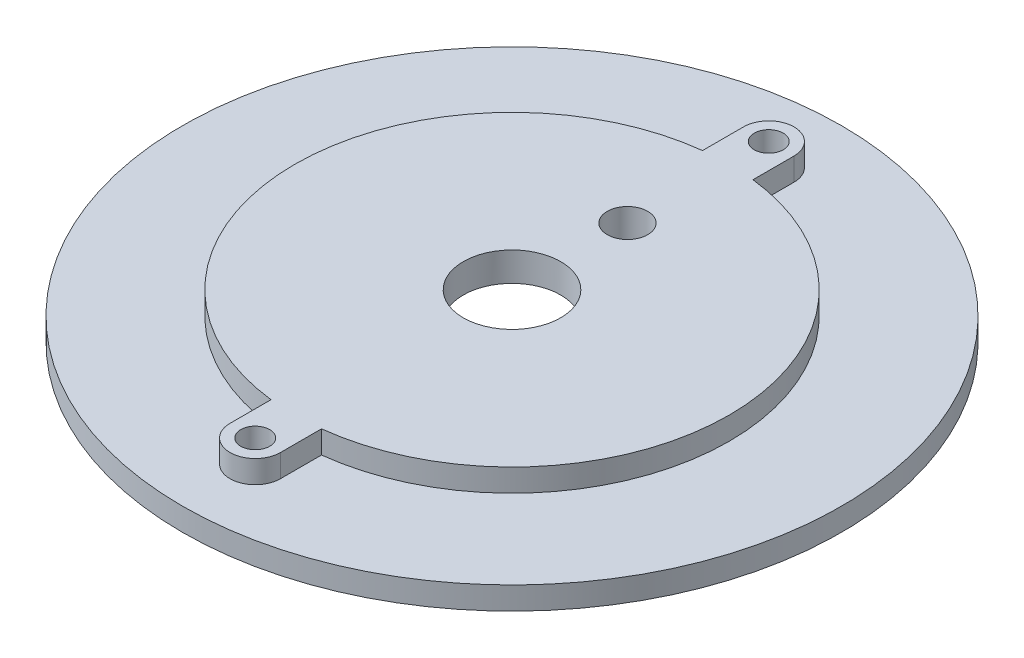
SolidWorks part; units mm, degrees
ref_plane "Front Plane" through (0, 0, 0) normal (0, 0, 1) x (1, 0, 0)
ref_plane "Top Plane" through (0, 0, 0) normal (0, 1, 0) x (1, 0, 0)
ref_plane "Right Plane" through (0, 0, 0) normal (1, 0, 0) x (0, 0, -1)
sketch "Sketch1" plane through (0, 0, 0) normal (0, 1, 0) x (1, 0, 0)
  line L0 (-2.18, -567.0979) -> (-2.18, 28219.6003) construction
  line L1 (2.18, -567.009) -> (2.18, 28219.6893) construction
  line L2 (-1013.5145, 24.355) -> (48986.4855, 24.355) construction
  line L3 (-1014.7713, -24.355) -> (1014.7713, -24.355) construction
  line L4 (-2.18, 22.175) -> (-2.18, -22.175)
  line L5 (2.18, -22.175) -> (2.18, 22.175)
  arc A1 (-2.18, 22.175) -> (2.18, 22.175) centre (0, 22.175) cw
  arc A2 (-2.18, -22.175) -> (2.18, -22.175) centre (0, -22.175) ccw
  dimension "D1" = 4.36
  dimension "D3" = 48.71
  dimension "D6" = 2.18
  dimension "D7" = 2.18
  dimension "D8" = 2.18
  dimension "D9" = 2.18
  dimension "D10" = 2.18
  dimension "D11" = 2.18
extrude "Boss-Extrude1" add sketch "Sketch1" along normal blind 1.96 contours L4 A2 L5 A1
sketch "Sketch2" plane through (0, 0, 0) normal (0, -1, 0) x (1, 0, 0)
  circle A0 centre (0, 0) radius 18.76
  dimension "D1" = 37.52
extrude "Boss-Extrude2" add sketch "Sketch2" against normal blind 1.96 contours A0
sketch "Sketch3" plane through (0, 0, 0) normal (0, -1, 0) x (1, 0, 0)
  circle A0 centre (0, 0) radius 28.4611
  dimension "D1" = 56.9223
extrude "Boss-Extrude3" add sketch "Sketch3" along normal blind 1.96
sketch "Sketch4" plane through (0, 1.96, 0) normal (0, 1, 0) x (1, 0, 0)
  circle A0 centre (0, 22.175) radius 1.25
  circle A1 centre (0, -22.175) radius 1.25
  arc A2 (-2.18, -22.175) -> (2.18, -22.175) centre (0, -22.175) ccw construction
  arc A3 (2.18, 22.175) -> (-2.18, 22.175) centre (0, 22.175) ccw construction
  dimension "D3" = 2.5
  dimension "D4" = 2.5
  dimension "D2" = 0
extrude "Cut-Extrude1" cut sketch "Sketch4" against normal up to next
sketch "Sketch5" plane through (0, 1.96, 0) normal (0, 1, 0) x (1, 0, 0)
  line L0 (0, 0) -> (0, 22.175) construction
  circle A0 centre (0, 0) radius 4.205
  circle A1 centre (0, 9.975) radius 1.75
  dimension "D1" = 8.41
  dimension "D2" = 3.5
  dimension "D3" = 9.975
extrude "Cut-Extrude2" cut sketch "Sketch5" against normal up to next
sketch "Sketch6" plane through (0, -1.96, 0) normal (0, -1, 0) x (1, 0, 0)
  circle A0 centre (0, 0) radius 6.75
  dimension "D1" = 13.5
extrude "Cut-Extrude3" cut sketch "Sketch6" against normal blind 1.42
equation "\"tabwidth\"=4.36"
equation "\"D1@Sketch1\"=\"tabwidth\""
equation "\"tablength\"=48.71"
equation "\"D3@Sketch1\"=\"tablength\""
equation "\"D6@Sketch1\"=\"tabwidth\"/2"
equation "\"D7@Sketch1\"=\"tabwidth\"/2"
equation "\"D8@Sketch1\"=\"tabwidth\"/2"
equation "\"D9@Sketch1\"=\"tabwidth\"/2"
equation "\"D10@Sketch1\"=\"tabwidth\"/2"
equation "\"D11@Sketch1\"=\"tabwidth\"/2"
equation "\"thread\"= 2.5"
equation "\"D4@Sketch4\"=\"thread\""
equation "\"D3@Sketch4\"=\"thread\""
